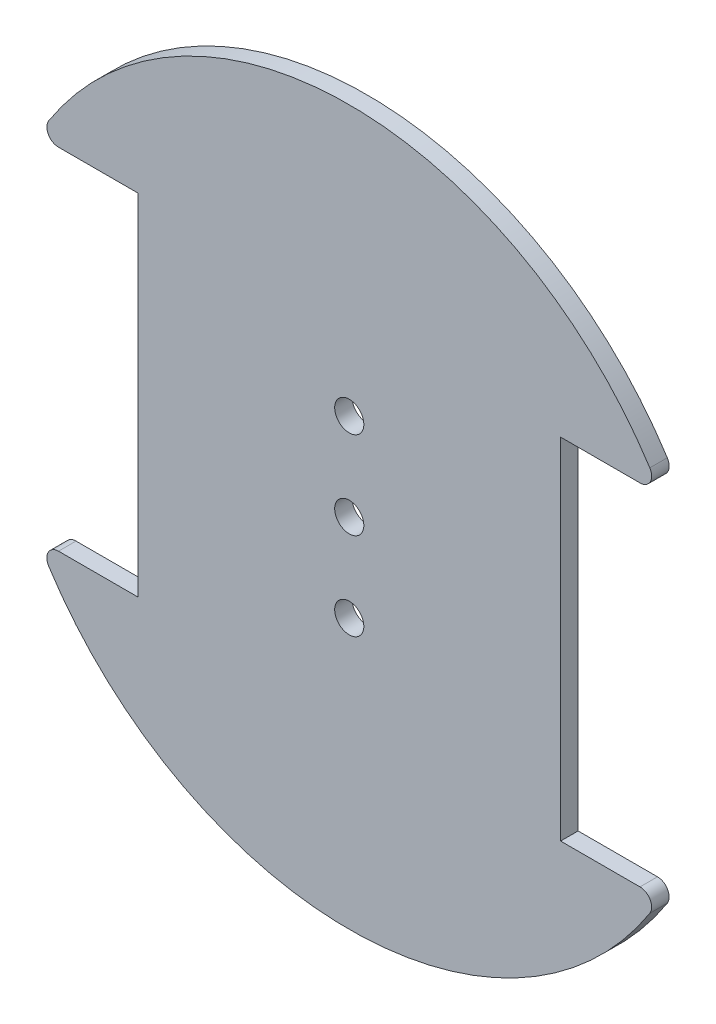
SolidWorks part; units mm, degrees
material "MDF"
ref_plane "Plano frontal" through (0, 0, 0) normal (0, 0, 1) x (1, 0, 0)
ref_plane "Plano superior" through (0, 0, 0) normal (0, 1, 0) x (1, 0, 0)
ref_plane "Plano direito" through (0, 0, 0) normal (1, 0, 0) x (0, 0, -1)
sketch "Esboço1" plane through (0, 0, 0) normal (0, 0, 1) x (1, 0, 0)
  line L0 (-72.5, 60) -> (-99.7309, 60)
  line L1 (0, -64) -> (0, 66.2069) construction
  line L2 (72.5, -60) -> (72.5, 60)
  line L3 (72.5, 60) -> (99.7309, 60)
  line L4 (-72.5, -60) -> (-72.5, 60)
  line L5 (72.5, -60) -> (-72.5, 60) construction
  line L6 (72.5, 60) -> (-72.5, -60) construction
  line L7 (72.5, -60) -> (99.7309, -60)
  line L8 (-72.5, -60) -> (-99.7309, -60)
  arc A0 (-103.0973, -66.1603) -> (103.0973, -66.1603) centre (0, 0) ccw
  arc A1 (103.0973, 66.1603) -> (-103.0973, 66.1603) centre (0, 0) ccw
  arc A2 (-103.0973, -66.1603) -> (-99.7309, -60) centre (-99.7309, -64) cw
  arc A3 (103.0973, -66.1603) -> (99.7309, -60) centre (99.7309, -64) ccw
  arc A4 (103.0973, 66.1603) -> (99.7309, 60) centre (99.7309, 64) cw
  arc A5 (-103.0973, 66.1603) -> (-99.7309, 60) centre (-99.7309, 64) ccw
  circle A7 centre (0, -30) radius 5
  circle A9 centre (0, 0) radius 5
  circle A11 centre (0, 30) radius 5
  point P16 (106.8, 60)
  dimension "D5" = 27.2309
  dimension "D16" = 10
  dimension "D2" = 4
  dimension "D3" = 72.5
  dimension "D4" = 72.5
  dimension "D6" = 27.2309
extrude "Ressalto-extrusão1" add sketch "Esboço1" along normal blind 6
sketch "Esboço4" plane through (0, 0, 0) normal (0, 0, -1) x (-1, 0, 0)
  line L2 (72.5, -21.5) -> (29.5, 21.5) construction
  line L3 (72.5, 21.5) -> (29.5, -21.5) construction
  line L4 (0, -60) -> (0, 60) construction
  line L5 (-72.5, 21.5) -> (-29.5, 21.5) construction
  line L6 (-72.5, 21.5) -> (-72.5, -21.5) construction
  line L7 (-72.5, -21.5) -> (-29.5, -21.5) construction
  line L8 (-29.5, 21.5) -> (-29.5, -21.5) construction
  line L9 (-72.5, 21.5) -> (-29.5, -21.5) construction
  line L10 (-72.5, -21.5) -> (-29.5, 21.5) construction
  line L11 (29.5, 21.5) -> (29.5, -21.5) construction
  line L12 (72.5, -21.5) -> (29.5, -21.5) construction
  line L13 (72.5, 21.5) -> (72.5, -21.5) construction
  line L14 (72.5, 21.5) -> (29.5, 21.5) construction
  point P4 (-51, 0)
  point P12 (51, 0)
  dimension "D1" = 43
  dimension "D2" = 43
